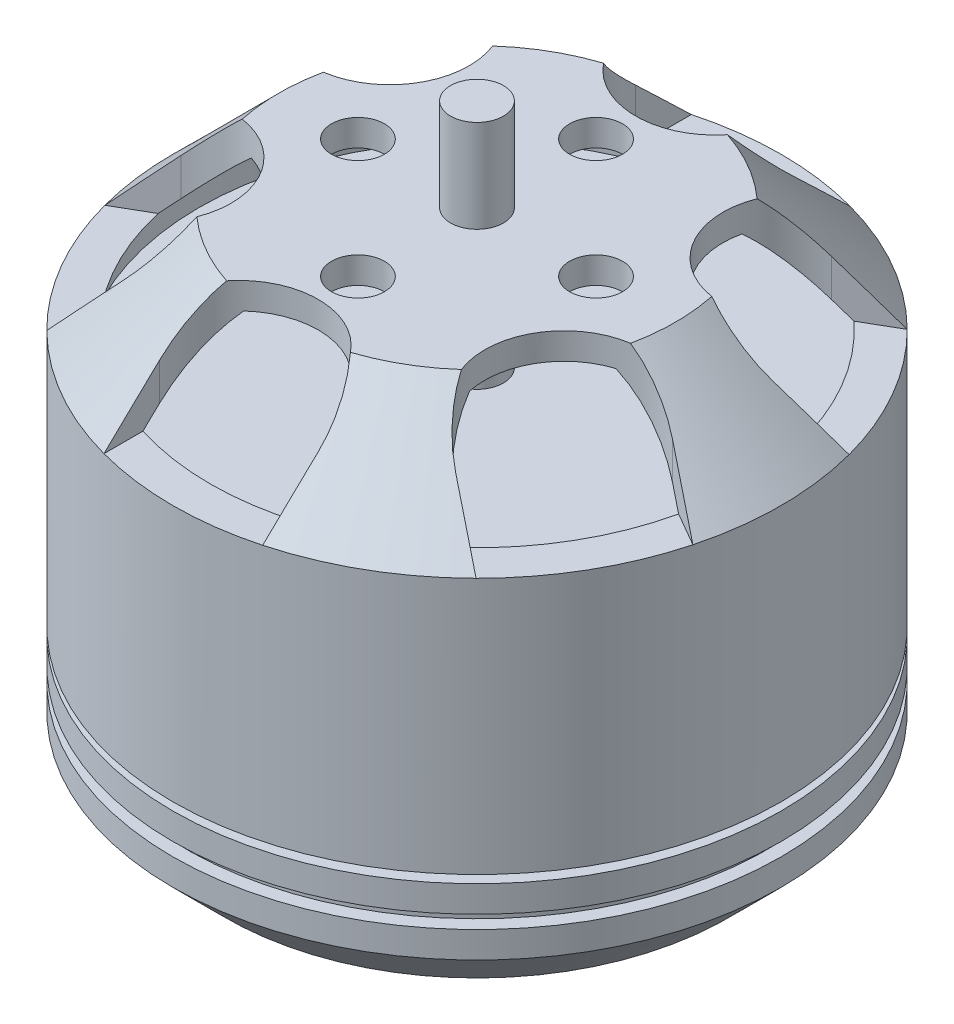
SolidWorks part; units mm, degrees
ref_plane "Front Plane" through (0, 0, 0) normal (0, 0, 1) x (1, 0, 0)
ref_plane "Top Plane" through (0, 0, 0) normal (0, 1, 0) x (1, 0, 0)
ref_plane "Right Plane" through (0, 0, 0) normal (1, 0, 0) x (0, 0, -1)
sketch "Sketch1" plane through (0, 0, 0) normal (0, 0, 1) x (1, 0, 0)
  line L0 (0, 22) -> (0, -1.8)
  line L1 (0, -1.8) -> (1, -1.8)
  line L2 (1, -1.8) -> (1, 0)
  line L8 (1, 0) -> (9.5, 0)
  line L9 (9.5, 0) -> (11.5, 2)
  line L10 (11.5, 2) -> (11.5, 3)
  line L11 (11.5, 14.5) -> (7.5, 18.5)
  line L12 (7.5, 18.5) -> (1, 18.5)
  line L13 (1, 18.5) -> (1, 22)
  line L14 (1, 22) -> (0, 22)
  line L15 (2, 17.5) -> (7.0858, 17.5)
  line L16 (7.0858, 17.5) -> (10.5, 14.0858)
  line L19 (10.5, 13.2606) -> (1, 13.2606)
  line L20 (1, 13.2606) -> (1, 16.5)
  line L21 (1, 16.5) -> (2, 16.5)
  line L22 (2, 16.5) -> (2, 17.5)
  line L23 (10.5, 14.0858) -> (10.5, 13.2606)
  line L24 (11.5, 4.8) -> (9.5, 4.8)
  line L25 (9.5, 4.8) -> (9.5, 4.5)
  line L26 (9.5, 4.5) -> (11.5, 4.5)
  line L27 (11.5, 3.5) -> (11, 3.5)
  line L28 (11, 3.5) -> (11, 3)
  line L29 (11, 3) -> (11.5, 3)
  line L30 (11.5, 4.8) -> (11.5, 14.5)
  line L31 (11.5, 3.5) -> (11.5, 4.5)
  dimension "D1" = 23.8
  dimension "D2" = 1.8
  dimension "D3" = 45
  dimension "D4" = 2
  dimension "D5" = 11.5
  dimension "D6" = 1
  dimension "D7" = 3.5
  dimension "D8" = 1
  dimension "D9" = 45
  dimension "D10" = 1
  dimension "D11" = 1
  dimension "D12" = 1
  dimension "D13" = 1
  dimension "D14" = 1
  dimension "D15" = 1
  dimension "D16" = 4
  dimension "D17" = 0.5
  dimension "D18" = 0.5
  dimension "D19" = 0.3
  dimension "D20" = 2
  dimension "D21" = 1
  dimension "D22" = 1
revolve "Revolve1" add sketch "Sketch1" angle 360 about L0
sketch "Sketch2" plane through (0, 18.5, 0) normal (0, 1, 0) x (1, 0, 0)
  line L0 (0, 0) -> (0, 9) construction
  line L1 (-3, 9) -> (-3, 16.0939)
  line L2 (-3, 16.0939) -> (3, 16.0939)
  line L3 (3, 16.0939) -> (3, 9)
  line L4 (15.4378, 5.4489) -> (9.2942, 1.9019)
  line L5 (12.4378, 10.6451) -> (15.4378, 5.4489)
  line L6 (6.2942, 7.0981) -> (12.4378, 10.6451)
  line L7 (12.4378, -10.6451) -> (6.2942, -7.0981)
  line L8 (15.4378, -5.4489) -> (12.4378, -10.6451)
  line L9 (9.2942, -1.9019) -> (15.4378, -5.4489)
  line L10 (-3, -16.0939) -> (-3, -9)
  line L11 (3, -16.0939) -> (-3, -16.0939)
  line L12 (3, -9) -> (3, -16.0939)
  line L13 (-15.4378, -5.4489) -> (-9.2942, -1.9019)
  line L14 (-12.4378, -10.6451) -> (-15.4378, -5.4489)
  line L15 (-6.2942, -7.0981) -> (-12.4378, -10.6451)
  line L16 (-12.4378, 10.6451) -> (-6.2942, 7.0981)
  line L17 (-15.4378, 5.4489) -> (-12.4378, 10.6451)
  line L18 (-9.2942, 1.9019) -> (-15.4378, 5.4489)
  circle A0 centre (0, 0) radius 4.5 construction
  circle A1 centre (0, 4.5) radius 1
  circle A2 centre (0, 0) radius 4.5 construction
  circle A3 centre (4.5, 0) radius 1
  circle A4 centre (0, 0) radius 4.5 construction
  circle A5 centre (0, -4.5) radius 1
  circle A6 centre (0, 0) radius 4.5 construction
  circle A7 centre (-4.5, 0) radius 1
  arc A8 (-3, 9) -> (3, 9) centre (0, 9) ccw
  arc A9 (6.2942, 7.0981) -> (9.2942, 1.9019) centre (7.7942, 4.5) ccw
  arc A10 (9.2942, -1.9019) -> (6.2942, -7.0981) centre (7.7942, -4.5) ccw
  arc A11 (3, -9) -> (-3, -9) centre (0, -9) ccw
  arc A12 (-6.2942, -7.0981) -> (-9.2942, -1.9019) centre (-7.7942, -4.5) ccw
  arc A13 (-9.2942, 1.9019) -> (-6.2942, 7.0981) centre (-7.7942, 4.5) ccw
  point P18 (0, 0)
  point P48 (0, 0)
  dimension "D1" = 9
  dimension "D3" = 2
  dimension "D5" = 6
  dimension "D2" = 9
  dimension "D4" = 4
  dimension "D6" = 6
extrude "Cut-Extrude1" cut sketch "Sketch2" against normal blind 4
sketch "Sketch3" plane through (0, 0, 0) normal (0, -1, 0) x (1, 0, 0)
  circle A0 centre (0, 0) radius 8 construction
  circle A1 centre (0, 0) radius 6 construction
  circle A2 centre (0, 6) radius 1
  circle A3 centre (0, -6) radius 1
  circle A6 centre (8, 0) radius 1
  circle A7 centre (-8, 0) radius 1
  dimension "D1" = 16
  dimension "D2" = 12
  dimension "D3" = 2
extrude "Cut-Extrude2" cut sketch "Sketch3" against normal blind 3
